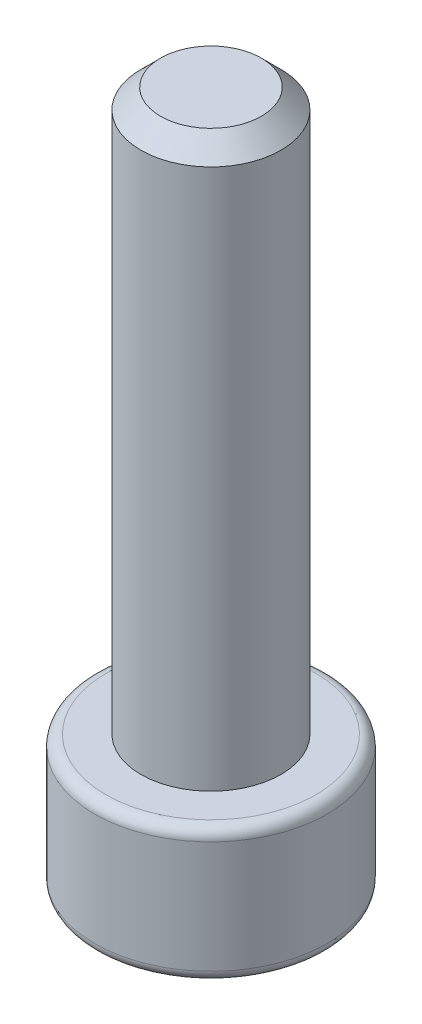
SolidWorks part; units mm, degrees
ref_plane "Front Plane" through (0, 0, 0) normal (0, 0, 1) x (1, 0, 0)
ref_plane "Top Plane" through (0, 0, 0) normal (0, 1, 0) x (1, 0, 0)
ref_plane "Right Plane" through (0, 0, 0) normal (1, 0, 0) x (0, 0, -1)
sketch "Sketch1" plane through (0, 0, 0) normal (0, 1, 0) x (1, 0, 0)
  circle A0 centre (0, 0) radius 4.15
  dimension "D1" = 8.3
extrude "Boss-Extrude1" add sketch "Sketch1" along normal blind 4.8
sketch "Sketch2" plane through (0, 4.8, 0) normal (0, 1, 0) x (1, 0, 0)
  circle A0 centre (0, 0) radius 2.5
  dimension "D1" = 5
extrude "Boss-Extrude2" add sketch "Sketch2" along normal blind 20
sketch "Sketch3" plane through (0, 0, 0) normal (0, -1, 0) x (1, 0, 0)
  line L1 (2.8868, 0) -> (1.4434, 2.5)
  line L2 (1.4434, 2.5) -> (-1.4434, 2.5)
  line L3 (-1.4434, 2.5) -> (-2.8868, 0)
  line L4 (-2.8868, 0) -> (-1.4434, -2.5)
  line L5 (-1.4434, -2.5) -> (1.4434, -2.5)
  line L6 (1.4434, -2.5) -> (2.8868, 0)
  circle A0 centre (0, 0) radius 2.5 construction
  dimension "D1" = 5
extrude "Cut-Extrude1" cut sketch "Sketch3" against normal blind 2.5 and the other way through all
chamfer "Chamfer1" distance 0.7 angle 45 1 edges at (0, 24.8, 2.5)
fillet "Fillet1" radius 0.4 2 edges at (0, 0, 4.15) (0, 4.8, 4.15)
